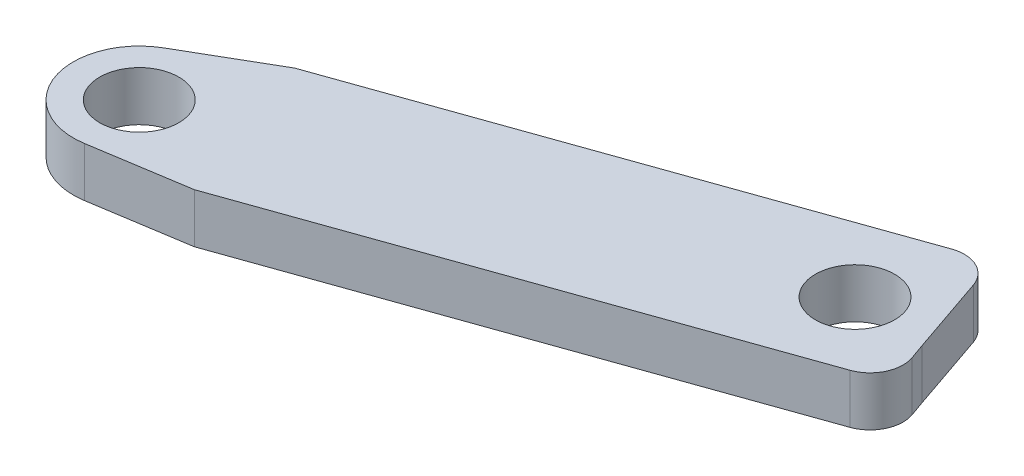
SolidWorks part; units mm, degrees
ref_plane "Front Plane" through (0, 0, 0) normal (0, 0, 1) x (1, 0, 0)
ref_plane "Top Plane" through (0, 0, 0) normal (0, 1, 0) x (1, 0, 0)
ref_plane "Right Plane" through (0, 0, 0) normal (1, 0, 0) x (0, 0, -1)
sketch "Sketch3" plane through (0, 0, 0) normal (0, 1, 0) x (1, 0, 0)
  line L10 (9.052, -11.6944) -> (-2.4947, -15.7823)
  line L11 (10.7207, -16.4077) -> (-0.826, -20.4957)
  line L12 (10.7207, -16.4077) -> (13.8538, -15.2985)
  line L13 (14.4628, -14.0221) -> (14.3007, -13.5642)
  line L14 (13.4874, -11.1951) -> (14.3007, -13.5642)
  line L15 (9.052, -11.6944) -> (12.2078, -10.5772)
  line L16 (-2.4947, -15.7823) -> (-2.7148, -15.9097)
  line L17 (-0.826, -20.4957) -> (-1.0772, -20.5352)
  line L18 (-3.706, -20.949) -> (-1.0772, -20.5352)
  line L19 (-2.7148, -15.9097) -> (-5.0184, -17.2421)
  circle A3 centre (-4.017, -18.9734) radius 1
  circle A4 centre (12.0074, -13.3002) radius 1
  arc A5 (13.8538, -15.2985) -> (14.4628, -14.0221) centre (13.5201, -14.3558) ccw
  arc A6 (13.4874, -11.1951) -> (12.2078, -10.5772) centre (12.5416, -11.5198) ccw
  arc A7 (-5.0184, -17.2421) -> (-3.706, -20.949) centre (-4.017, -18.9734) ccw
  dimension "D1" = 2
  dimension "D2" = 2
  dimension "D3" = 9.052
  dimension "D4" = 10.7207
  dimension "D5" = 12.0074
  dimension "D6" = 12.2078
  dimension "D7" = 12.5416
  dimension "D8" = 13.4874
  dimension "D9" = 13.5201
  dimension "D10" = 14.3007
  dimension "D11" = 0.826
  dimension "D12" = 1.0772
  dimension "D13" = 2.7148
  dimension "D14" = 10.5772
  dimension "D18" = 13.3002
extrude "Boss-Extrude2" add sketch "Sketch3" along normal blind 1.5
other "Move Face1" face at (12.0074, 1.5, 14.3002) face at (-4.017, 1.5, 19.9734) parameters "D1"=0.2
